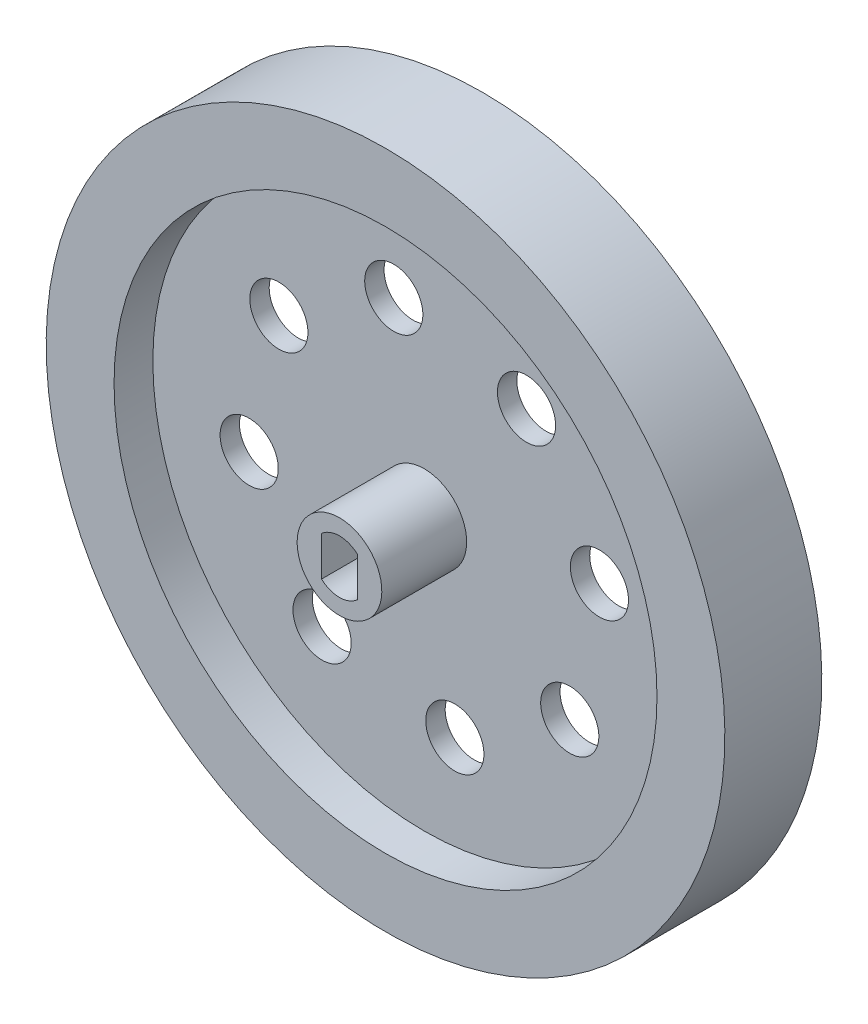
SolidWorks part; units mm, degrees
material "Custom Plastic"
ref_plane "Front Plane" through (0, 0, 0) normal (0, 0, 1) x (1, 0, 0)
ref_plane "Top Plane" through (0, 0, 0) normal (0, 1, 0) x (1, 0, 0)
ref_plane "Right Plane" through (0, 0, 0) normal (1, 0, 0) x (0, 0, -1)
sketch "Sketch1" plane through (0, 0, 0) normal (1, 0, 0) x (0, 0, -1)
  line L0 (0, 0) -> (-9.75, 0)
  line L1 (-9.75, 0) -> (-9.75, 4.3673)
  line L2 (-9.75, 4.3673) -> (-1, 4.3673)
  line L3 (-1, 4.3673) -> (-1, 28)
  line L4 (-1, 28) -> (-5, 28)
  line L5 (-5, 28) -> (-5, 35)
  line L6 (5, 35) -> (-5, 35)
  line L9 (0, 0) -> (0, 65.1462) construction
  line L10 (0, 0) -> (-9.75, 0) construction
  line L11 (1, 28) -> (1, 0)
  line L14 (5, 28) -> (5, 35)
  line L15 (1, 28) -> (5, 28)
  line L16 (1, 0) -> (0, 0)
  line L17 (0, 0) -> (-9.75, 0) construction
  dimension "D1" = 4
  dimension "D2" = 10
  dimension "D3" = 35
  dimension "D4" = 7
  dimension "D5" = 8.75
revolve "Revolve1" add sketch "Sketch1" angle 360 about L0
sketch "Sketch2" plane through (0, 0, -1) normal (0, 0, -1) x (-1, 0, 0)
  circle A0 centre (-10.5439, 15) radius 3
  circle A1 centre (3.1509, 18.0623) radius 3
  circle A2 centre (15, 10.5439) radius 3
  circle A3 centre (18.0623, -3.1509) radius 3
  circle A4 centre (10.5439, -15) radius 3
  circle A5 centre (-3.1509, -18.0623) radius 3
  circle A6 centre (-15, -10.5439) radius 3
  circle A7 centre (-18.0623, 3.1509) radius 3
  point P21 (0, 0)
  dimension "D2" = 8
  dimension "D1" = 15
extrude "Cut-Extrude1" cut sketch "Sketch2" against normal blind 2
sketch "Sketch3" plane through (0, 0, 9.75) normal (0, 0, 1) x (1, 0, 0)
  line L0 (0, -2.75) -> (0, 2.75) construction
  line L1 (1.85, -2.0347) -> (1.85, 2.0347)
  line L2 (-1.85, -2.0347) -> (-1.85, 2.0347)
  line L3 (1.85, -2.75) -> (1.85, 2.75) construction
  line L4 (-1.85, -2.75) -> (-1.85, 2.75) construction
  arc A0 (-1.85, -2.0347) -> (1.85, -2.0347) centre (0, 0) ccw
  arc A1 (1.85, 2.0347) -> (-1.85, 2.0347) centre (0, 0) ccw
  dimension "D1" = 1.85
  dimension "D2" = 1.85
extrude "Cut-Extrude2" cut sketch "Sketch3" against normal offset from surface (8.75 mm away) 2 up to face at (15.0623, 3.1509, -1)
sketch "Sketch4" plane through (0, 0, -1) normal (0, 0, -1) x (-1, 0, 0)
  circle A0 centre (0, 0) radius 0.95
extrude "Cut-Extrude3" cut sketch "Sketch4" against normal blind 2
